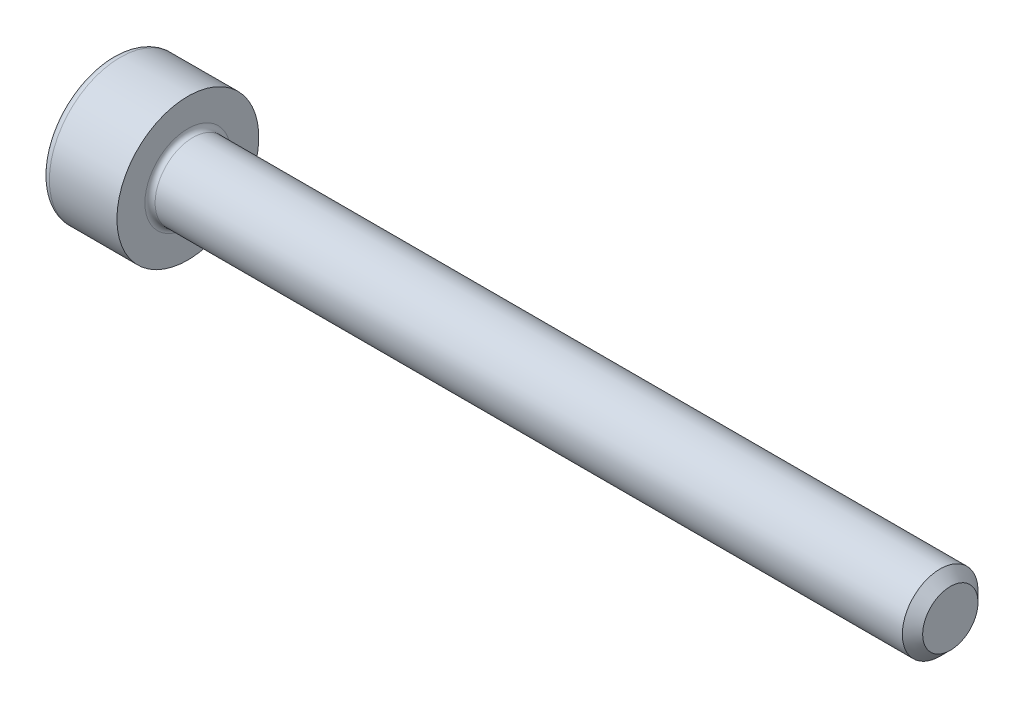
SolidWorks part; units mm, degrees
ref_plane "Спереди" through (0, 0, 0) normal (0, 0, 1) x (1, 0, 0)
ref_plane "Сверху" through (0, 0, 0) normal (0, 1, 0) x (1, 0, 0)
ref_plane "Справа" through (0, 0, 0) normal (1, 0, 0) x (0, 0, -1)
sketch "Sketch1" plane through (0, 0, 0) normal (0, 0, 1) x (1, 0, 0)
  line L0 (0, 0) -> (1.4887, 0)
  line L1 (1.4887, 0) -> (1.4887, 1.3957)
  line L2 (1.4887, 1.3957) -> (0, 1.3957)
  line L3 (0, 1.3957) -> (0, 0)
  line L4 (1.4887, 0) -> (16.4887, 0)
  line L5 (16.4887, 0) -> (16.4887, 0.7444)
  line L6 (16.4887, 0.7444) -> (1.4887, 0.7444)
  dimension "D1" = 15
revolve "Revolve1" add sketch "Sketch1" angle 360 about L0
fillet "Fillet1" radius 0.1 1 edges at (1.4887, 0, 0.7444)
fillet "Fillet2" radius 0.16 1 edges at (0, 0, 1.3957)
chamfer "Chamfer1" distance 0.2 angle 45 1 edges at (16.4887, 0, 0.7444)
sketch "Sketch2" plane through (0, 0, 0) normal (-1, 0, 0) x (0, 0, 1)
  line L1 (0, 0.8776) -> (-0.76, 0.4388)
  line L2 (-0.76, 0.4388) -> (-0.76, -0.4388)
  line L3 (-0.76, -0.4388) -> (0, -0.8776)
  line L4 (0, -0.8776) -> (0.76, -0.4388)
  line L5 (0.76, -0.4388) -> (0.76, 0.4388)
  line L6 (0.76, 0.4388) -> (0, 0.8776)
  circle A0 centre (0, 0) radius 0.76 construction
extrude "Extrude1" cut sketch "Sketch2" against normal blind 0.7
